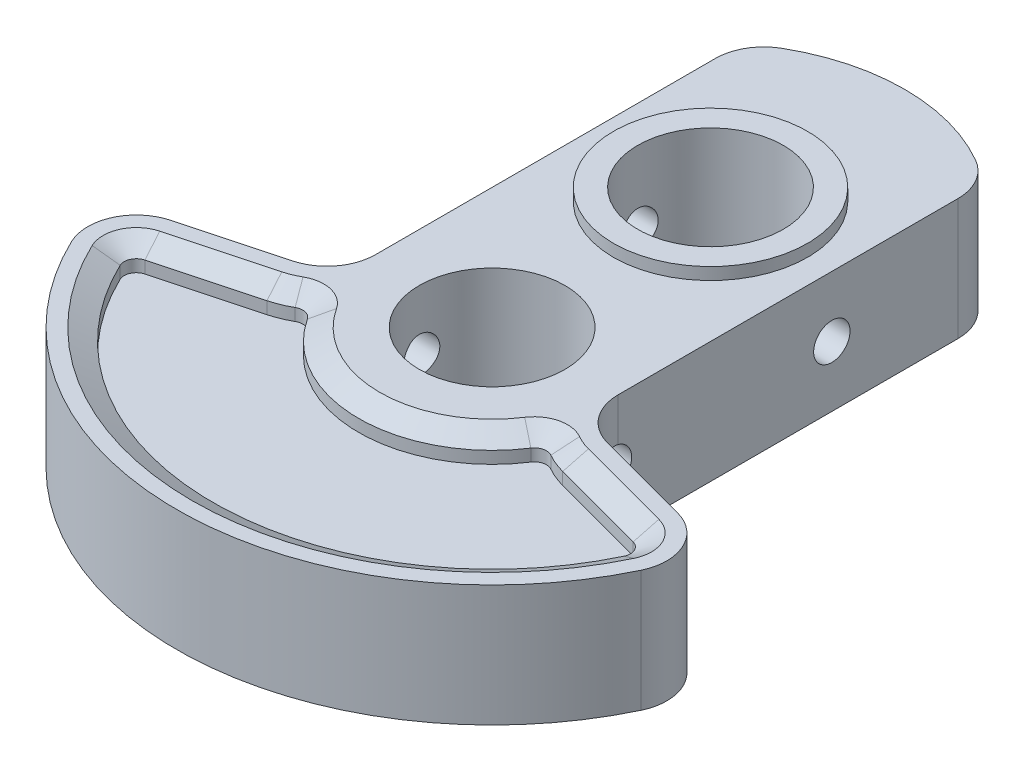
SolidWorks part; units mm, degrees
material "Gray Cast Iron"
ref_plane "Front Plane" through (0, 0, 0) normal (0, 0, 1) x (1, 0, 0)
ref_plane "Top Plane" through (0, 0, 0) normal (0, 1, 0) x (1, 0, 0)
ref_plane "Right Plane" through (0, 0, 0) normal (1, 0, 0) x (0, 0, -1)
sketch "Sketch1" plane through (0, 0, 0) normal (0, 1, 0) x (1, 0, 0)
  line L0 (0, 34) -> (0, -33.4771) construction
  line L1 (-10, 30.49) -> (-10, -2.6795)
  line L2 (10, 30.49) -> (10, -2.6795)
  line L3 (-10, 34) -> (-10, -33.4771) construction
  line L4 (10, 34) -> (10, -33.4771) construction
  line L5 (-10, -2.6795) -> (-25.1141, -6.7293)
  line L6 (10, -2.6795) -> (25.1141, -6.7293)
  arc A0 (10, 30.49) -> (-10, 30.49) centre (0, 18) ccw
  arc A3 (-25.1141, -6.7293) -> (25.1141, -6.7293) centre (0, 0) ccw
  dimension "D2" = 32
  dimension "D5" = 26
  dimension "D1" = 18
  dimension "D6" = 75
  dimension "D7" = 75
  dimension "D8" = 33.1695
  dimension "D3" = 10
  dimension "D4" = 10
extrude "Boss-Extrude1" add sketch "Sketch1" along normal mid plane 10
fillet "Fillet1" radius 4 6 edges at (-25.1141, 0, 6.7293) (25.1141, 0, 6.7293) (-10, 0, 2.6795) (-10, 0, -30.49) (10, 0, -30.49) (10, 0, 2.6795)
sketch "Sketch2" plane through (0, -5, 0) normal (0, -1, 0) x (1, 0, 0)
  circle A0 centre (0, 0) radius 8
  dimension "D1" = 16
extrude "Boss-Extrude2" add sketch "Sketch2" along normal blind 1
sketch "Sketch3" plane through (0, 5, 0) normal (0, 1, 0) x (1, 0, 0)
  circle A0 centre (0, 18) radius 8
  dimension "D1" = 16
  dimension "D2" = 18
extrude "Boss-Extrude3" add sketch "Sketch3" along normal blind 1
sketch "Sketch4" plane through (0, -6, 0) normal (0, -1, 0) x (1, 0, 0)
  circle A0 centre (0, 0) radius 6
  circle A1 centre (0, -18) radius 6
  dimension "D1" = 12
  dimension "D2" = 12
extrude "Cut-Extrude1" cut sketch "Sketch4" against normal through all
sketch "Sketch5" plane through (0, 5, 0) normal (0, 1, 0) x (1, 0, 0)
  line L4 (12.1883, -6.3717) -> (20.1197, -8.4969)
  line L5 (-20.1197, -8.4969) -> (-12.1883, -6.3717)
  line L6 (12.1883, -6.3717) -> (20.1197, -8.4969)
  line L7 (-20.1197, -8.4969) -> (-12.1883, -6.3717)
  arc A5 (-9.2082, -6.0173) -> (9.2082, -6.0173) centre (0, 0) ccw
  arc A6 (9.2082, -6.0173) -> (10.5397, -5.6951) centre (10.0453, -6.5644) cw
  arc A7 (-10.5397, -5.6951) -> (-9.2082, -6.0173) centre (-10.0453, -6.5644) cw
  arc A10 (20.7637, -9.8929) -> (20.1197, -8.4969) centre (19.8609, -9.4628) ccw
  arc A11 (7, 0.3898) -> (12.1883, -6.3717) centre (14, 0.3898) ccw
  arc A12 (-20.7637, -9.8929) -> (20.7637, -9.8929) centre (0, 0) ccw
  arc A13 (-20.1197, -8.4969) -> (-20.7637, -9.8929) centre (-19.8609, -9.4628) ccw
  arc A14 (-12.1883, -6.3717) -> (-7, 0.3898) centre (-14, 0.3898) ccw
  arc A15 (20.7637, -9.8929) -> (20.1197, -8.4969) centre (19.8609, -9.4628) ccw
  arc A16 (10.5397, -5.6951) -> (12.1883, -6.3717) centre (14, 0.3898) ccw
  arc A17 (-20.7637, -9.8929) -> (20.7637, -9.8929) centre (0, 0) ccw
  arc A18 (-20.1197, -8.4969) -> (-20.7637, -9.8929) centre (-19.8609, -9.4628) ccw
  arc A19 (-12.1883, -6.3717) -> (-10.5397, -5.6951) centre (-14, 0.3898) ccw
  dimension "D2" = 22
  dimension "D3" = 1
  dimension "D1" = 3
extrude "Cut-Extrude2" cut sketch "Sketch5" against normal blind 2
chamfer "Chamfer1" distance 1 angle 60 10 edges at (11.3424, 5, 6.0861) (9.8101, 5, 5.5924) (16.154, 5, 7.4343) (0, 5, 11) (20.7689, 5, 9.044) (-9.8101, 5, 5.5924) (0, 5, 23) (-11.3424, 5, 6.0861) (-20.7689, 5, 9.044) (-16.154, 5, 7.4343)
mirror "Mirror5" about plane through (0, 0, 0) normal (0, 1, 0) of "Cut-Extrude2"
chamfer "Chamfer2" distance 1 angle 60 10 edges at (-11.3424, -5, 6.0861) (-16.154, -5, 7.4343) (-9.8101, -5, 5.5924) (-20.7689, -5, 9.044) (0, -5, 11) (0, -5, 23) (9.8101, -5, 5.5924) (20.7689, -5, 9.044) (11.3424, -5, 6.0861) (16.154, -5, 7.4343)
sketch "Sketch6" plane through (0, 0, 0) normal (1, 0, 0) x (0, 0, -1)
  circle A0 centre (0, 0) radius 1.5
  circle A1 centre (18, 0) radius 1.5
  dimension "D2" = 3
  dimension "D1" = 18
extrude "Cut-Extrude3" cut sketch "Sketch6" against normal through all both and the other way through all
sketch "Sketch7" plane through (0, 5, 0) normal (0, 1, 0) x (1, 0, 0)
  line L0 (0, 0) -> (0, 48.1607)
